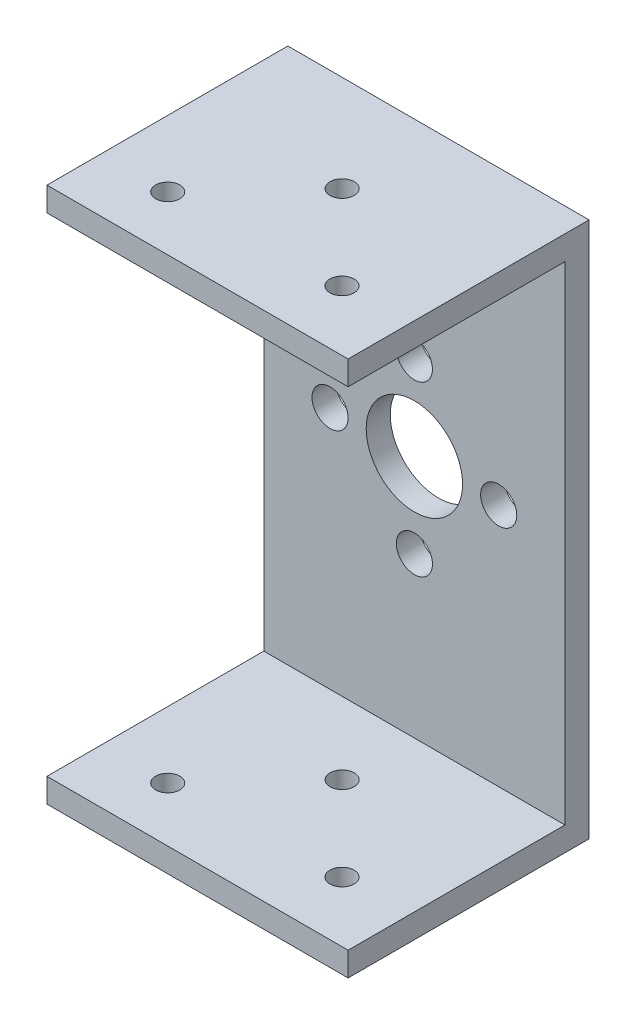
SolidWorks part; units mm, degrees
material "Plain Carbon Steel"
ref_plane "Front Plane" through (0, 0, 0) normal (0, 0, 1) x (1, 0, 0)
ref_plane "Top Plane" through (0, 0, 0) normal (0, 1, 0) x (1, 0, 0)
ref_plane "Right Plane" through (0, 0, 0) normal (1, 0, 0) x (0, 0, -1)
sketch "Sketch1" plane through (0, 0, 0) normal (0, 0, 1) x (1, 0, 0)
  line L1 (-12.6748, 30.5029) -> (12.3252, 30.5029)
  line L2 (-12.6748, 30.5029) -> (-12.6748, -9.9971)
  line L3 (-12.6748, -9.9971) -> (12.3252, -9.9971)
  line L4 (12.3252, 30.5029) -> (12.3252, -9.9971)
  dimension "D1" = 25
  dimension "D2" = 40.5
extrude "Boss-Extrude1" add sketch "Sketch1" along normal blind 2
sketch "Sketch2" plane through (0, 30.5029, 0) normal (0, 1, 0) x (1, 0, 0)
  line L1 (-12.6748, 0) -> (12.3252, 0)
  line L2 (-12.6748, 0) -> (-12.6748, -20)
  line L3 (-12.6748, -20) -> (12.3252, -20)
  line L4 (12.3252, 0) -> (12.3252, -20)
  dimension "D1" = 25
  dimension "D2" = 20
extrude "Boss-Extrude2" add sketch "Sketch2" along normal blind 2
sketch "Sketch3" plane through (0, -9.9971, 0) normal (0, -1, 0) x (-1, 0, 0)
  line L1 (-12.3252, 0) -> (12.6748, 0)
  line L2 (-12.3252, 0) -> (-12.3252, -20)
  line L3 (-12.3252, -20) -> (12.6748, -20)
  line L4 (12.6748, 0) -> (12.6748, -20)
  dimension "D1" = 25
  dimension "D2" = 20
extrude "Boss-Extrude3" add sketch "Sketch3" along normal blind 2
sketch "Sketch5" plane through (0, 0, 0) normal (0, 0, -1) x (-1, 0, 0)
  line L0 (12.6748, 32.5029) -> (12.6748, -11.9971) construction
  line L1 (12.6748, -11.9971) -> (-12.3252, -11.9971) construction
  circle A0 centre (0.1748, 10.2529) radius 4
  dimension "D1" = 12.5
  dimension "D2" = 22.25
extrude "Cut-Extrude2" cut sketch "Sketch5" against normal blind 21
sketch "Sketch6" plane through (0, 0, 0) normal (0, 0, -1) x (-1, 0, 0)
  circle A0 centre (7.1748, 10.2529) radius 1.5
  circle A1 centre (0.1748, 10.2529) radius 4 construction
  circle A2 centre (0.1748, 3.2529) radius 1.5
  circle A3 centre (-6.8252, 10.2529) radius 1.5
  circle A4 centre (0.1748, 17.2529) radius 1.5
  point P13 (0.1748, 10.2529)
  dimension "D1" = 7
  dimension "D2" = 4
extrude "Cut-Extrude3" cut sketch "Sketch6" against normal blind 21
sketch "Sketch7" plane through (0, -11.9971, 0) normal (0, -1, 0) x (-1, 0, 0)
  line L0 (12.6748, -20) -> (12.6748, 0) construction
  line L1 (-12.3252, -20) -> (12.6748, -20) construction
  circle A0 centre (7.1748, -15.4732) radius 1
  circle A1 centre (-6.8172, -15) radius 1
  circle A2 centre (0.1748, -8) radius 1
  dimension "D1" = 5.5
  dimension "D3" = 7
  dimension "D2" = 14
  dimension "D4" = 12
extrude "Cut-Extrude4" cut sketch "Sketch7" against normal blind 55
